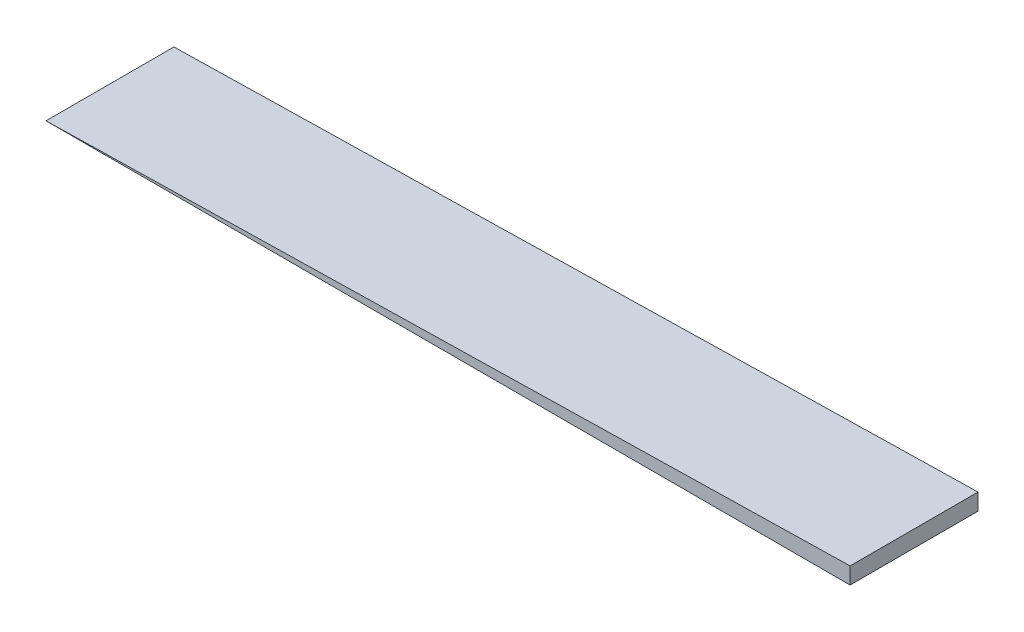
SolidWorks part; units mm, degrees
ref_plane "Front Plane" through (0, 0, 0) normal (0, 0, 1) x (1, 0, 0)
ref_plane "Top Plane" through (0, 0, 0) normal (0, 1, 0) x (1, 0, 0)
ref_plane "Right Plane" through (0, 0, 0) normal (1, 0, 0) x (0, 0, -1)
sketch "Sketch1" plane through (0, 0, 0) normal (0, 0, 1) x (1, 0, 0)
  line L0 (0, 0) -> (558.8, 0)
  line L1 (558.8, 0) -> (558.8, 11.5198)
  line L2 (558.8, 11.5198) -> (0, 0)
  dimension "D1" = 558.8
  dimension "D2" = 1.181
extrude "Boss-Extrude1" add sketch "Sketch1" along normal mid plane 88.9
